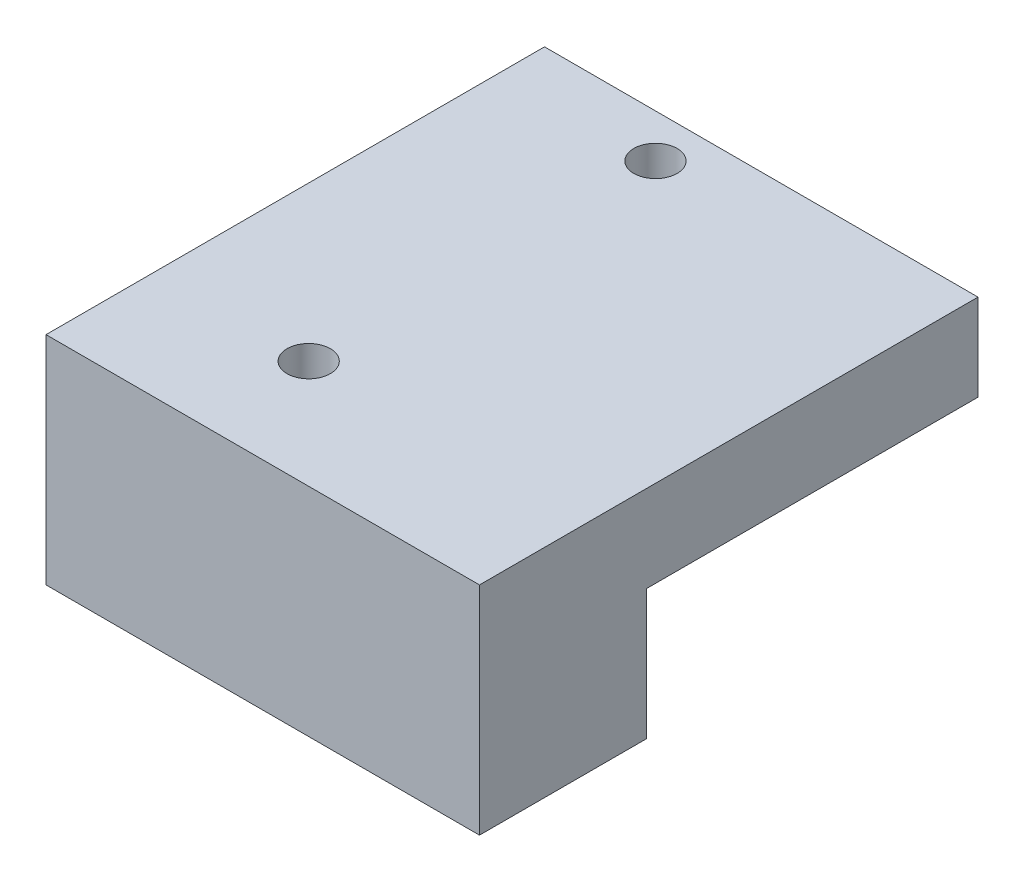
SolidWorks part; units mm, degrees
material "ABS"
ref_plane "Front Plane" through (0, 0, 0) normal (0, 0, 1) x (1, 0, 0)
ref_plane "Top Plane" through (0, 0, 0) normal (0, 1, 0) x (1, 0, 0)
ref_plane "Right Plane" through (0, 0, 0) normal (1, 0, 0) x (0, 0, -1)
sketch "Sketch1" plane through (0, 0, 0) normal (0, 1, 0) x (1, 0, 0)
  line L1 (10, -11.5) -> (-10, -11.5)
  line L2 (10, -11.5) -> (10, 11.5)
  line L3 (10, 11.5) -> (-10, 11.5)
  line L4 (-10, -11.5) -> (-10, 11.5)
  line L5 (10, -11.5) -> (-10, 11.5) construction
  line L6 (10, 11.5) -> (-10, -11.5) construction
  point P0 (0, 0)
  dimension "D1" = 20
  dimension "D2" = 23
extrude "Boss-Extrude1" add sketch "Sketch1" along normal blind 10
sketch "Sketch15" plane through (0, 0, 0) normal (0, -1, 0) x (1, 0, 0)
  line L0 (0, -11.5) -> (-7, -11.5)
  line L1 (10, -11.5) -> (-10, -11.5) construction
  line L2 (0, -11.5) -> (7, -11.5)
  line L3 (-7, -11.5) -> (-7, 8.5)
  line L4 (-7, 8.5) -> (7, 8.5)
  line L5 (7, 8.5) -> (7, -11.5)
  dimension "D1" = 7
  dimension "D2" = 7
  dimension "D3" = 20
extrude "Cut-Extrude13" cut sketch "Sketch15" against normal blind 7
sketch "Sketch16" plane through (-10, 0, 0) normal (-1, 0, 0) x (0, 0, 1)
  line L0 (-11.5, 0) -> (-1.5, 0) construction
  line L1 (-11.5, 0) -> (11.5, 0) construction
  circle A0 centre (-1.5, 0) radius 4.55
  dimension "D2" = 9.1
  dimension "D1" = 10
extrude "Cut-Extrude14" cut sketch "Sketch16" against normal blind 7
sketch "Sketch18" plane through (-7, 0, 0) normal (1, 0, 0) x (0, 0, -1)
  line L0 (-3.05, 0) -> (-5.775, 0)
  line L1 (-8.5, 0) -> (-3.05, 0) construction
  line L2 (6.05, 0) -> (8.775, 0)
  line L3 (6.05, 0) -> (11.5, 0) construction
  line L4 (-8.5, 7) -> (11.5, 7) construction
  line L5 (-5.775, 0) -> (8.775, 0)
  line L6 (-5.775, 0) -> (-5.775, 7)
  line L7 (-5.775, 7) -> (8.775, 7)
  line L8 (8.775, 0) -> (8.775, 7)
  arc A0 (6.05, 0) -> (-3.05, 0) centre (1.5, 0) ccw construction
extrude "Cut-Extrude16" cut sketch "Sketch18" against normal blind 1.5 contours L6 L5 L8 L7
sketch "Sketch20" plane through (0, 10, 0) normal (0, 1, 0) x (1, 0, 0)
  line L0 (-10, 11.5) -> (-2.88, 11.5) construction
  line L1 (10, 11.5) -> (-10, 11.5) construction
  line L2 (-2.88, 11.5) -> (-2.88, 9.5) construction
  line L3 (-2.88, 9.5) -> (-2.88, -6.5) construction
  circle A0 centre (-2.88, 9.5) radius 1
  circle A1 centre (-2.88, -6.5) radius 1
  dimension "D4" = 2
  dimension "D5" = 2
  dimension "D1" = 7.12
  dimension "D2" = 2
  dimension "D3" = 16
extrude "Cut-Extrude18" cut sketch "Sketch20" against normal blind 5
sketch "Sketch21" plane through (10, 0, 0) normal (1, 0, 0) x (0, 0, -1)
  line L0 (11.5, 0) -> (11.5, 6)
  line L1 (11.5, 10) -> (11.5, 0) construction
  line L2 (11.5, 6) -> (-3.8, 6)
  line L4 (-3.8, 6) -> (11.5, 6)
  line L5 (-3.8, 6) -> (-3.8, 0)
  line L6 (-3.8, 0) -> (11.5, 0)
  line L7 (11.5, 6) -> (11.5, 0)
  dimension "D1" = 6
  dimension "D2" = 15.3
extrude "Cut-Extrude19" cut sketch "Sketch21" against normal blind 5 contours L5 L4 L7 L6
